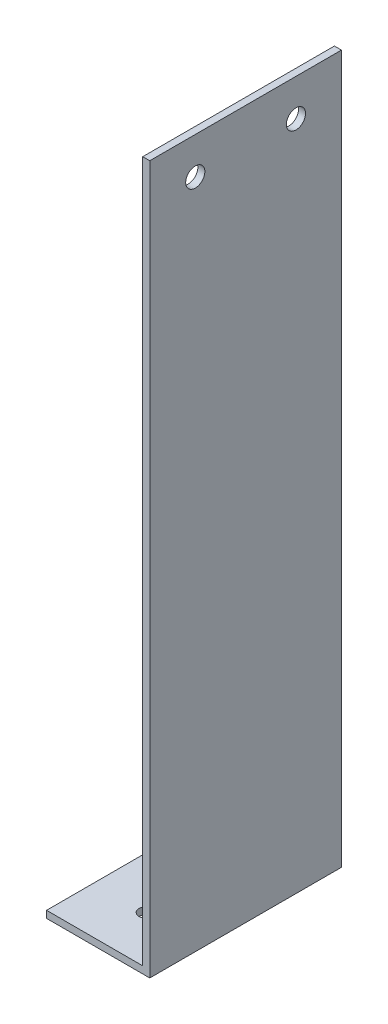
SolidWorks part; units mm, degrees
material "AISI 1020 Acero laminado en frío"
ref_plane "Alzado" through (0, 0, 0) normal (0, 0, 1) x (1, 0, 0)
ref_plane "Planta" through (0, 0, 0) normal (0, 1, 0) x (1, 0, 0)
ref_plane "Vista lateral" through (0, 0, 0) normal (1, 0, 0) x (0, 0, -1)
sketch "Croquis1" plane through (0, 0, 0) normal (0, 0, 1) x (1, 0, 0)
  line L0 (0, 0) -> (0, 480)
  line L1 (0, 0) -> (-70, 0)
  line L2 (-4.7625, 4.7625) -> (-70, 4.7625)
  line L3 (-4.7625, 4.7625) -> (-4.7625, 480)
  line L4 (-70, 0) -> (-70, 4.7625)
  line L5 (0, 480) -> (-4.7625, 480)
  dimension "D2" = 480
  dimension "D3" = 70
  dimension "D1" = 4.7625
extrude "Saliente-Extruir1" add sketch "Croquis1" along normal mid plane 130
sketch "Croquis2" plane through (0, 0, 0) normal (0, -1, 0) x (-1, 0, 0)
  line L0 (-20.5629, 0) -> (137.2136, 0) construction
  line L1 (35, -65) -> (35, 65) construction
  line L2 (70, -65) -> (0, -65) construction
  line L3 (70, 65) -> (0, 65) construction
  circle A0 centre (35, -32.5) radius 4.7625
  circle A3 centre (35, 32.5) radius 4.7625
  point P11 (0, 0)
  point P12 (0, 0)
  dimension "D1" = 9.525
  dimension "D3" = 32.5
  dimension "D8" = 32.5
extrude "Cortar-Extruir1" cut sketch "Croquis2" against normal blind 130
sketch "Croquis3" plane through (0, 0, 0) normal (1, 0, 0) x (0, 0, -1)
  line L0 (0, 315.912) -> (0, 117.859) construction
  line L1 (101.994, 455) -> (-93.1823, 455) construction
  line L3 (-65, 480) -> (65, 480) construction
  circle A0 centre (-34.1313, 455) radius 6.5
  circle A1 centre (34.1312, 455) radius 6.5
  dimension "D1" = 13
  dimension "D2" = 34.1313
  dimension "D3" = 25
extrude "Cortar-Extruir2" cut sketch "Croquis3" against normal blind 130
